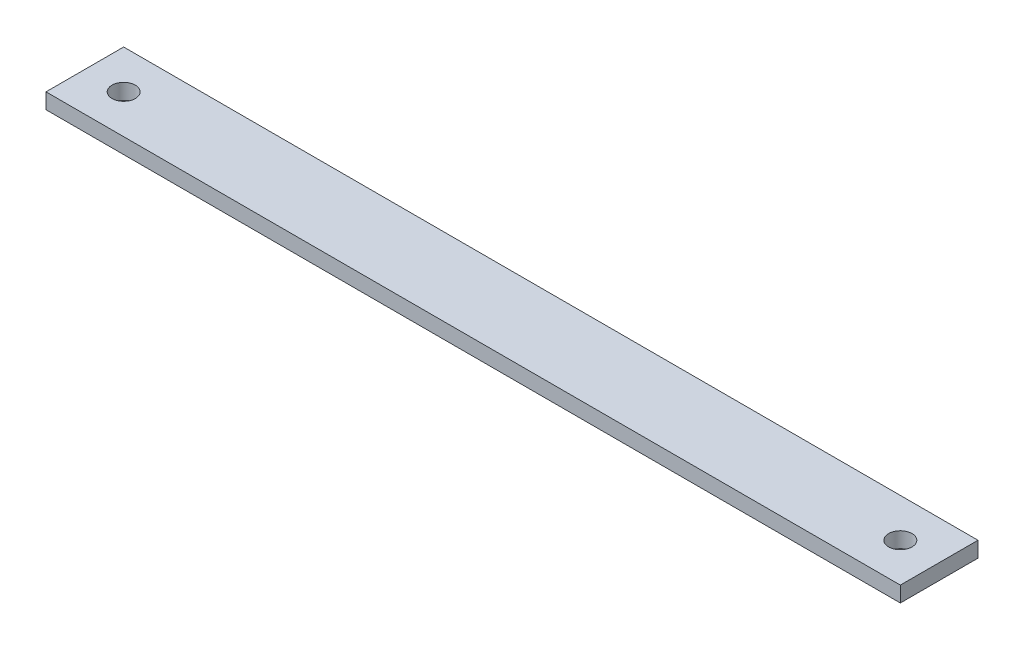
SolidWorks part; units mm, degrees
ref_plane "Front Plane" through (0, 0, 0) normal (0, 0, 1) x (1, 0, 0)
ref_plane "Top Plane" through (0, 0, 0) normal (0, 1, 0) x (1, 0, 0)
ref_plane "Right Plane" through (0, 0, 0) normal (1, 0, 0) x (0, 0, -1)
sketch "Sketch3" plane through (0, 0, 0) normal (0, 1, 0) x (1, 0, 0)
  line L0 (-55, 0) -> (55, 0) construction
  line L1 (-55, -5) -> (55, -5)
  line L2 (-55, -5) -> (-55, 5)
  line L3 (-55, 5) -> (55, 5)
  line L4 (55, -5) -> (55, 5)
  line L5 (-55, -5) -> (55, 5) construction
  line L6 (-55, 5) -> (55, -5) construction
  line L7 (0, 0) -> (0, 16.9167) construction
  circle A0 centre (-50, 0) radius 1.5
  circle A1 centre (50, 0) radius 1.5
  point P0 (0, 0)
  dimension "D4" = 3
  dimension "D1" = 10
  dimension "D2" = 110
  dimension "D3" = 5
extrude "Boss-Extrude1" add sketch "Sketch3" along normal blind 2
